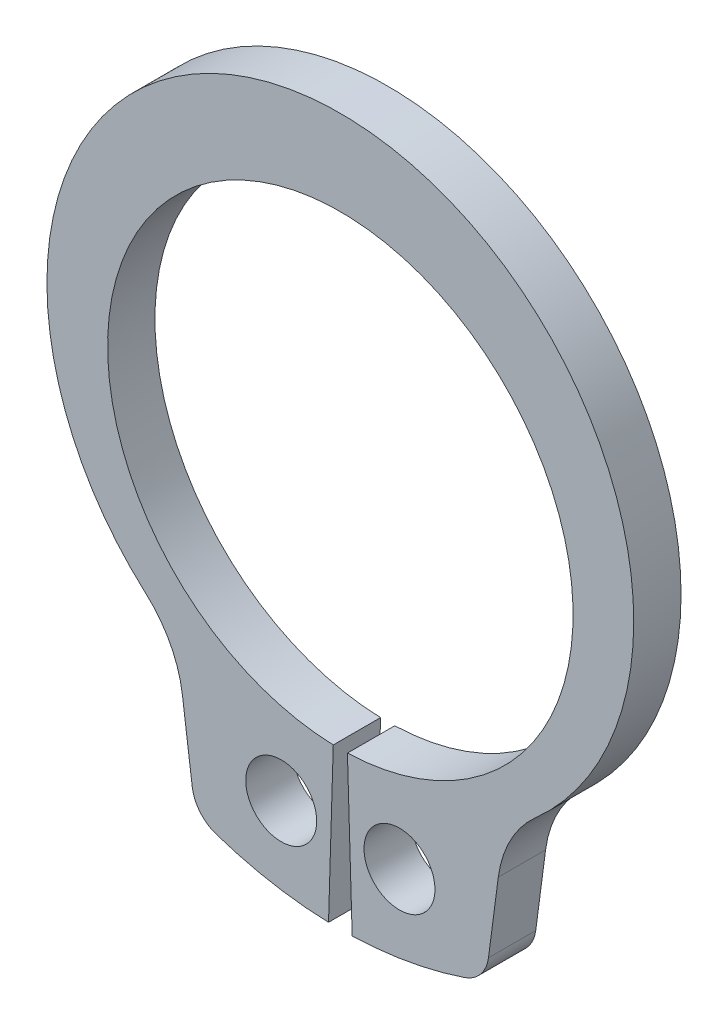
SolidWorks part; units mm, degrees
ref_plane "Plane1" through (0, 0, 0) normal (0, 0, 1) x (1, 0, 0)
ref_plane "Plane2" through (0, 0, 0) normal (0, 1, 0) x (1, 0, 0)
ref_plane "Plane3" through (0, 0, 0) normal (1, 0, 0) x (0, 0, -1)
extrude "Body" add sketch "BodySke" against normal blind 1
sketch "BodySke" plane through (0, 0, 0) normal (0, 0, 1) x (1, 0, 0)
  line L0 (-1.5431, 0) -> (1.5431, 0) construction
  line L1 (0, 0) -> (0, 6.72) construction
  line L2 (0.1496, -4.9177) -> (0.25, -8.2162)
  line L3 (-0.1496, -4.9177) -> (-0.25, -8.2162)
  line L4 (0, 0) -> (5.7155, -5.9078) construction
  line L5 (0, 0) -> (-5.7155, -5.9078) construction
  line L7 (3.3389, -5.5949) -> (3.1307, -7.1762)
  line L8 (-3.3389, -5.5949) -> (-3.1307, -7.1762)
  circle A0 centre (0, 0) radius 4.92 construction
  arc A1 (0.1496, -4.9177) -> (-0.1496, -4.9177) centre (0, 0) ccw
  arc A2 (4.0467, -4.1829) -> (-4.0467, -4.1829) centre (0, 0.5176) ccw construction
  arc A3 (0.25, -8.2162) -> (2.6268, -7.789) centre (0, 0) ccw
  arc A4 (4.1223, -4.1167) -> (3.3389, -5.5949) centre (5.7155, -5.9078) ccw
  arc A5 (-3.3389, -5.5949) -> (-4.1223, -4.1167) centre (-5.7155, -5.9078) ccw
  arc A6 (-2.6268, -7.789) -> (-0.25, -8.2162) centre (0, 0) ccw
  arc A7 (4.1223, -4.1167) -> (-4.1223, -4.1167) centre (0, 0.5176) ccw
  arc A8 (-3.3232, -5.7139) -> (3.3232, -5.7139) centre (0, 0) ccw construction
  circle A9 centre (1.25, -6.4907) radius 0.75
  circle A10 centre (-1.25, -6.4907) radius 0.75
  arc A11 (3.1307, -7.1762) -> (2.6268, -7.789) centre (2.3871, -7.0783) cw
  arc A12 (-3.1307, -7.1762) -> (-2.6268, -7.789) centre (-2.3871, -7.0783) ccw
  point P28 (3.0717, -7.6245)
  point P31 (-3.0717, -7.6245)
  dimension "GrooveDia" = 9.84
  dimension "D3" = 0.75
  dimension "LugRad" = 8.22
  dimension "HoleOffsetRad" = 6.61
  dimension "HoleDia" = 1.5
  dimension "D2" = 15
  dimension "LargeRad" = 6.72
  dimension "SmallRad" = 5.82
  dimension "Gap" = 0.5
  dimension "SmallAngle" = 88.105
  dimension "HoleSpacing" = 2.5
sketch "Clipboard" plane through (0, 0, 0) normal (0, 0, 1) x (1, 0, 0)
  line L0 (0, 0) -> (1.8, 0)
  line L1 (0, 0) -> (0, 0.9)
  line L2 (0, 0) -> (0, -3.3)
  circle A0 centre (0, 0) radius 0.75
  circle A1 centre (0, 0) radius 5
  dimension "HoleDia" = 1.5
  dimension "ShaftDia" = 10
  dimension "LargeSection" = 1.8
  dimension "SmallSection" = 0.9
  dimension "LugSection" = 3.3
sketch "NotSke" plane through (0, 0, 0) normal (0, 0, 1) x (1, 0, 0)
  line L0 (1.25, -5.7407) -> (1.25, -7.2407)
  line L1 (1.25, -7.2407) -> (-1.25, -7.2407)
  line L2 (-1.25, -7.2407) -> (-1.25, -5.7407)
  line L3 (-1.25, -5.7407) -> (1.25, -5.7407)
  circle A0 centre (1.25, -6.4907) radius 0.75 construction
  circle A1 centre (-1.25, -6.4907) radius 0.75 construction
extrude "Notch" [suppressed] cut sketch "NotSke" against normal through all
sketch "UnlSke" plane through (0, 0, 0) normal (0, 0, 1) x (1, 0, 0)
  line L0 (-2.4603, -7.8432) -> (-1.4726, -4.6945)
  line L1 (2.4603, -7.8432) -> (1.4726, -4.6945)
  arc A0 (1.4726, -4.6945) -> (-1.4726, -4.6945) centre (0, 0) ccw
  arc A1 (2.4603, -7.8432) -> (-2.4603, -7.8432) centre (0, 0) ccw
  arc A2 (0.25, -8.2162) -> (2.6268, -7.789) centre (0, 0) ccw construction
  arc A3 (0.1496, -4.9177) -> (-0.1496, -4.9177) centre (0, 0) ccw construction
  circle A4 centre (-1.25, -6.4907) radius 0.75 construction
  circle A5 centre (1.25, -6.4907) radius 0.75 construction
extrude "Unlug" [suppressed] add sketch "UnlSke" against normal through all
equation "' \"ShaftDia@Clipboard\" = 3"
equation "' \"Thickness@Body\" = 0.4"
equation "' \"GrooveDia@BodySke\" = 2.8"
equation "' \"LugSection@Clipboard\" = 1.9"
equation "' \"LargeSection@Clipboard\" = 0.8"
equation "' \"HoleDia@Clipboard\" = 1.0"
equation "' \"ShaftDia@Clipboard\" = 10"
equation "' \"Thickness@Body\" = 1.0"
equation "' \"GrooveDia@BodySke\" = 9.6"
equation "' \"LugSection@Clipboard\" = 3.3"
equation "' \"LargeSection@Clipboard\" = 1.8"
equation "' \"HoleDia@Clipboard\" = 1.5"
equation "\"SmallSection@Clipboard\" = \"LargeSection@Clipboard\" * 0.5"
equation "\"Gap@BodySke\" =  \"Thickness@Body\" / 2"
equation "\"LargeRad@BodySke\" =  \"GrooveDia@BodySke\" / 2 +  \"LargeSection@Clipboard\""
equation "\"SmallRad@BodySke\" =  \"GrooveDia@BodySke\" / 2 +  \"SmallSection@Clipboard\""
equation "\"LugRad@BodySke\" = \"GrooveDia@BodySke\" / 2 + \"LugSection@Clipboard\""
equation "\"HoleOffsetRad@BodySke\" = (  \"ShaftDia@Clipboard\" / 2 + \"LugRad@BodySke\" ) / 2"
equation "\"HoleSpacing@BodySke\" = \"Gap@BodySke\"  * 2 +  \"HoleDia@Clipboard\""
equation "\"HoleDia@BodySke\" =  \"HoleDia@Clipboard\""
equation "\"SmallAngle@BodySke\" = atn(\"HoleSpacing@BodySke\" / 2 / sqr(\"HoleOffsetRad@BodySke\"  * \"HoleOffsetRad@BodySke\" - (\"HoleSpacing@BodySke\" / 2) * (\"HoleSpacing@BodySke\" / 2) ))  * 7 *  (\"LargeRad@BodySke\" / \"SmallRad@BodySke\")* ( 180 / 3.141593)"
